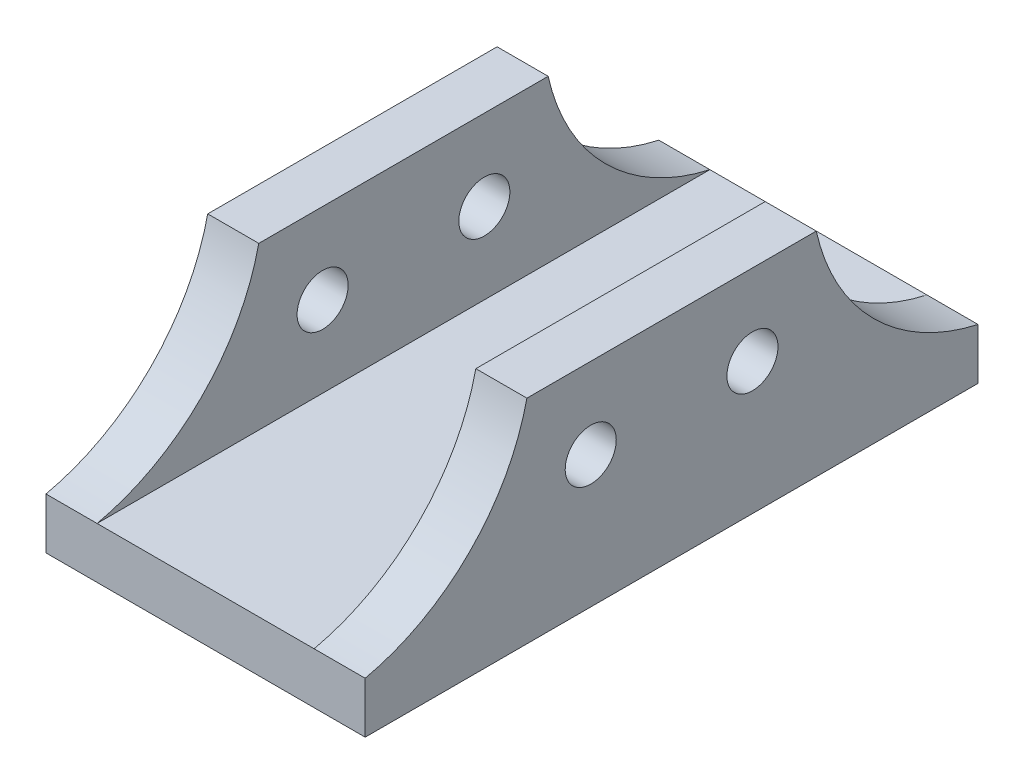
SolidWorks part; units mm, degrees
ref_plane "Front Plane" through (0, 0, 0) normal (0, 0, 1) x (1, 0, 0)
ref_plane "Top Plane" through (0, 0, 0) normal (0, 1, 0) x (1, 0, 0)
ref_plane "Right Plane" through (0, 0, 0) normal (1, 0, 0) x (0, 0, -1)
sketch "Sketch8" plane through (0, 0, 0) normal (1, 0, 0) x (0, 0, -1)
  line L0 (0, 0) -> (0, -61.0213) construction
  line L1 (-72, 0) -> (72, 0)
  line L2 (-72, 0) -> (-72, 50)
  line L3 (-72, 50) -> (72, 50)
  line L4 (72, 0) -> (72, 50)
  circle A0 centre (-19, 31) radius 6
  circle A1 centre (19, 31) radius 6
  point P11 (0, 0)
  dimension "D5" = 12
  dimension "D1" = 144
  dimension "D2" = 50
  dimension "D3" = 38
  dimension "D4" = 31
extrude "Boss-Extrude5" add sketch "Sketch8" along normal mid plane 75
sketch "Sketch9" plane through (0, 0, 72) normal (0, 0, 1) x (1, 0, 0)
  line L0 (37.5, 50) -> (-37.5, 50) construction
  line L1 (37.5, 50) -> (37.5, 0) construction
  line L2 (-25.5, 50) -> (25.5, 50)
  line L3 (-25.5, 50) -> (-25.5, 12)
  line L4 (-25.5, 12) -> (25.5, 12)
  line L5 (25.5, 50) -> (25.5, 12)
  line L6 (37.5, 0) -> (-37.5, 0) construction
  line L7 (-37.5, 50) -> (-37.5, 0) construction
  dimension "D1" = 12
  dimension "D2" = 12
  dimension "D3" = 12
extrude "Cut-Extrude1" cut sketch "Sketch9" against normal through all
sketch "Sketch10" plane through (37.5, 0, 0) normal (1, 0, 0) x (0, 0, -1)
  line L1 (0, 0) -> (0, 31) construction
  line L4 (-72, 50) -> (-34, 50)
  line L5 (72, 50) -> (-72, 50) construction
  line L6 (72, 0) -> (72, 50) construction
  line L7 (72, 50) -> (34, 50)
  line L8 (72, 12) -> (72, 50)
  line L9 (-72, 12) -> (-72, 50)
  arc A1 (34, 50) -> (72, 12) centre (82.8161, 60.8161) ccw
  arc A2 (-34, 50) -> (-72, 12) centre (-82.8161, 60.8161) cw
  dimension "D2" = 50
  dimension "D1" = 12
extrude "Cut-Extrude2" cut sketch "Sketch10" against normal through all
